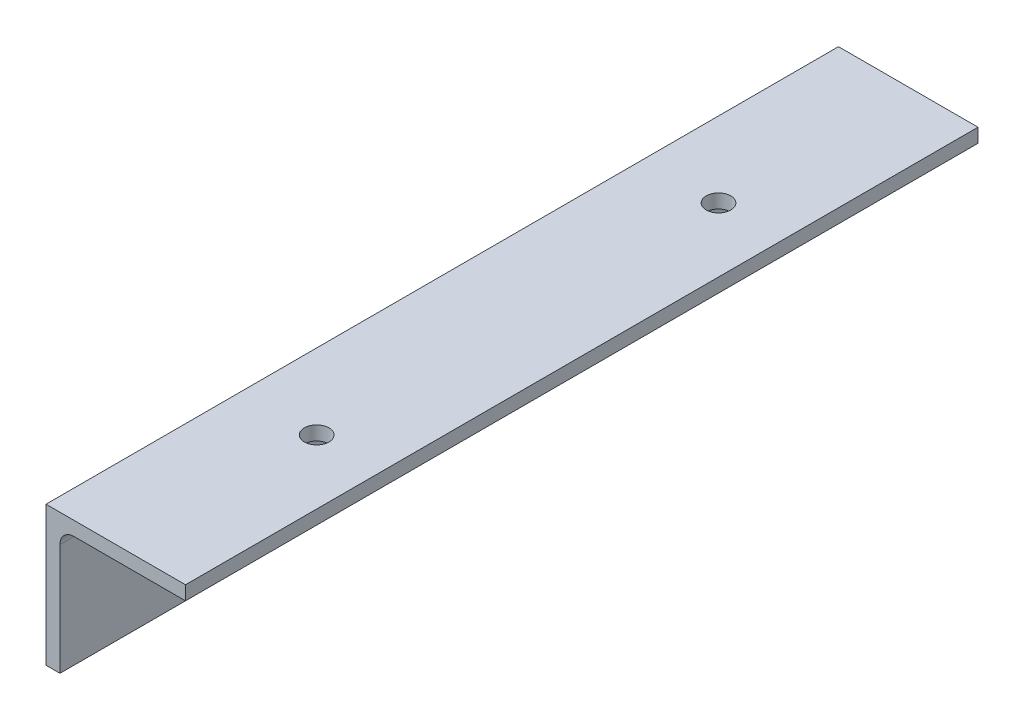
SolidWorks part; units mm, degrees
material "AISI 304"
ref_plane "Спереди" through (0, 0, 0) normal (0, 0, 1) x (1, 0, 0)
ref_plane "Сверху" through (0, 0, 0) normal (0, 1, 0) x (1, 0, 0)
ref_plane "Справа" through (0, 0, 0) normal (1, 0, 0) x (0, 0, -1)
sketch "Эскиз1" plane through (0, 0, 0) normal (0, 0, 1) x (1, 0, 0)
  line L0 (0, 0) -> (50, 0)
  line L1 (50, 0) -> (50, -5)
  line L2 (50, -5) -> (5, -5)
  line L3 (5, -5) -> (5, -50)
  line L4 (5, -50) -> (0, -50)
  line L5 (0, -50) -> (0, 0)
  dimension "D1" = 50
  dimension "D2" = 50
  dimension "D3" = 5
  dimension "D4" = 5
extrude "Бобышка-Вытянуть1" add sketch "Эскиз1" along normal mid plane 284
fillet "Скругление1" radius 5 1 edges at (5, -5, 0)
sketch "Эскиз2" plane through (0, 0, 0) normal (0, 1, 0) x (1, 0, 0)
  line L1 (50, -142) -> (50, 142) construction
  circle A7 centre (27, 72) radius 4.4
  dimension "D1" = 8.8
  dimension "D2" = 72
  dimension "D3" = 23
extrude "Вырез-Вытянуть1" cut sketch "Эскиз2" against normal blind 10
pattern_linear "Линейный массив1" [suppressed] count 1 spacing 140
mirror "Зеркальное отражение1" about plane through (0, 0, 0) normal (0, 0, 1) of "Линейный массив1", "Вырез-Вытянуть1"
